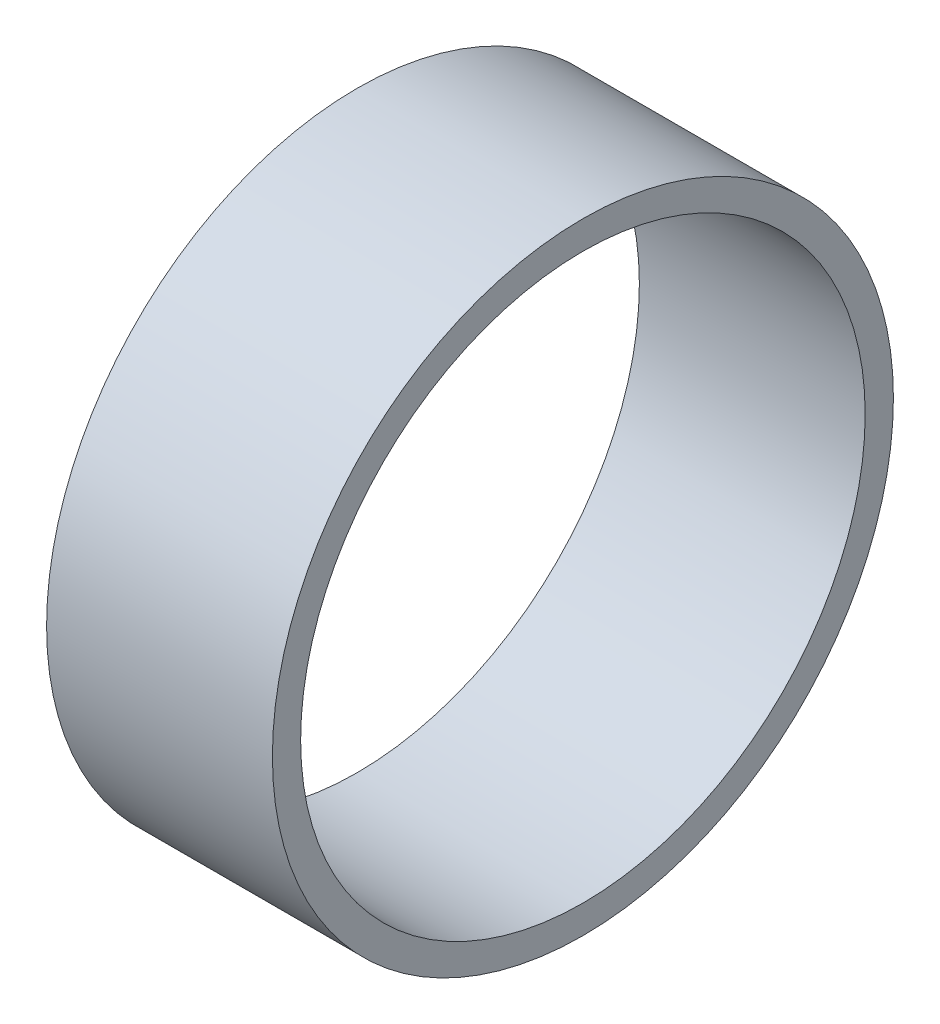
SolidWorks part; units mm, degrees
material "45"
ref_plane "前视基准面" through (0, 0, 0) normal (0, 0, 1) x (1, 0, 0)
ref_plane "上视基准面" through (0, 0, 0) normal (0, 1, 0) x (1, 0, 0)
ref_plane "右视基准面" through (0, 0, 0) normal (1, 0, 0) x (0, 0, -1)
sketch "草图1" plane through (0, 0, 0) normal (1, 0, 0) x (0, 0, -1)
  circle A0 centre (0, 0) radius 27.5
  circle A1 centre (0, 0) radius 25
  dimension "D1" = 55
  dimension "D2" = 50
extrude "凸台-拉伸1" add sketch "草图1" along normal blind 20
